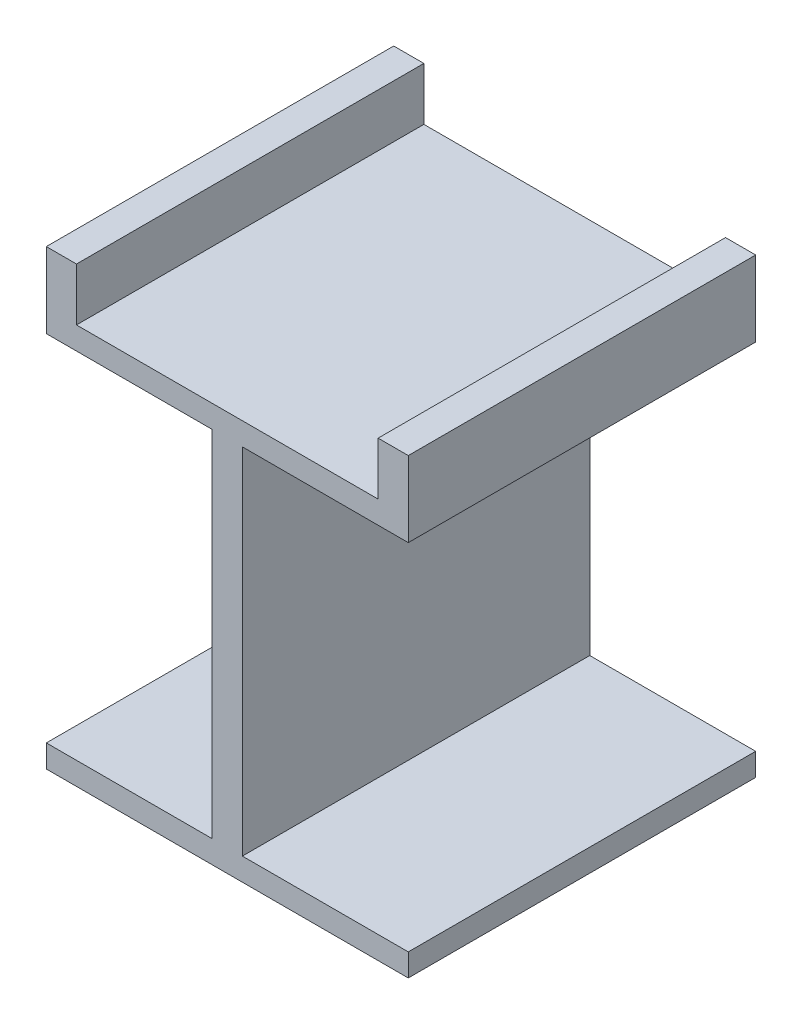
SolidWorks part; units mm, degrees
material "1060 Alaşım"
ref_plane "Ön Düzlem" through (0, 0, 0) normal (0, 0, 1) x (1, 0, 0)
ref_plane "Üst Düzlem" through (0, 0, 0) normal (0, 1, 0) x (1, 0, 0)
ref_plane "Sağ Düzlem" through (0, 0, 0) normal (1, 0, 0) x (0, 0, -1)
sketch "Çizim1" plane through (0, 0, 0) normal (0, 1, 0) x (1, 0, 0)
  line L1 (-24, 23.035) -> (24, 23.035)
  line L2 (-24, 23.035) -> (-24, -23.035)
  line L3 (-24, -23.035) -> (24, -23.035)
  line L4 (24, 23.035) -> (24, -23.035)
  line L5 (-24, 23.035) -> (24, -23.035) construction
  line L6 (-24, -23.035) -> (24, 23.035) construction
  point P0 (0, 0)
  dimension "D1" = 46.07
  dimension "D2" = 48
extrude "Yükseklik-Ekstrüzyon1" add sketch "Çizim1" along normal blind 3
sketch "Çizim2" plane through (0, 3, 0) normal (0, 1, 0) x (1, 0, 0)
  line L0 (24, 23.035) -> (-24, 23.035) construction
  line L1 (-2, 23.035) -> (2, 23.035)
  line L2 (-2, 23.035) -> (-2, -23.035)
  line L3 (-2, -23.035) -> (2, -23.035)
  line L4 (2, 23.035) -> (2, -23.035)
  line L5 (-2, 23.035) -> (2, -23.035) construction
  line L6 (-2, -23.035) -> (2, 23.035) construction
  point P0 (0, 0)
  dimension "D1" = 4
extrude "Yükseklik-Ekstrüzyon2" add sketch "Çizim2" along normal blind 50
ref_plane "Düzlem1" through (0, 26.5, 0) normal (0, 1, 0) x (1, 0, 0)
mirror "Aynalama1" about plane through (0, 26.5, 0) normal (0, 1, 0) of "Yükseklik-Ekstrüzyon1"
sketch "Çizim3" plane through (0, 53, 0) normal (0, 1, 0) x (1, 0, 0)
  line L0 (-24, -23.035) -> (24, -23.035) construction
  line L1 (24, 23.035) -> (20, 23.035)
  line L2 (24, 23.035) -> (24, -23.035)
  line L3 (24, -23.035) -> (20, -23.035)
  line L4 (20, 23.035) -> (20, -23.035)
  dimension "D1" = 4
extrude "Yükseklik-Ekstrüzyon3" add sketch "Çizim3" along normal blind 7
mirror "Aynalama2" about plane through (0, 0, 0) normal (1, 0, 0) of "Yükseklik-Ekstrüzyon3"
